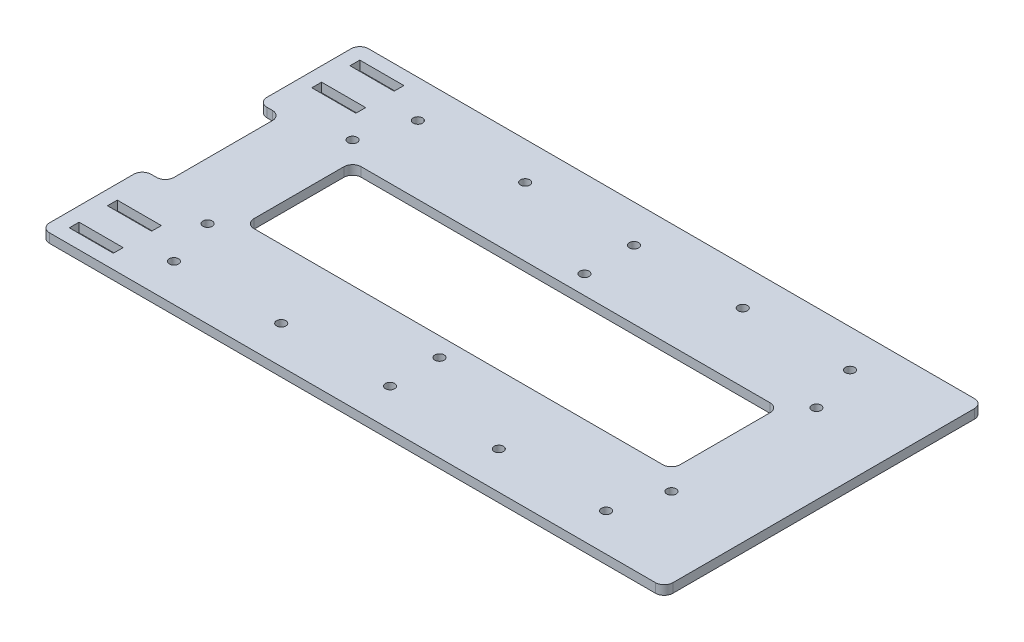
SolidWorks part; units mm, degrees
ref_plane "Front Plane" through (0, 0, 0) normal (0, 0, 1) x (1, 0, 0)
ref_plane "Top Plane" through (0, 0, 0) normal (0, 1, 0) x (1, 0, 0)
ref_plane "Right Plane" through (0, 0, 0) normal (1, 0, 0) x (0, 0, -1)
sketch "Sketch1" plane through (0, 0, 0) normal (0, 1, 0) x (1, 0, 0)
  line L1 (107.5, -55) -> (-107.5, -55)
  line L2 (107.5, -55) -> (107.5, 55)
  line L3 (107.5, 55) -> (-107.5, 55)
  line L4 (-107.5, -55) -> (-107.5, 55)
  line L5 (107.5, -55) -> (-107.5, 55) construction
  line L6 (107.5, 55) -> (-107.5, -55) construction
  point P0 (0, 0)
  dimension "D1" = 215
  dimension "D2" = 110
extrude "Boss-Extrude1" add sketch "Sketch1" along normal blind 3.175
sketch "Sketch2" plane through (0, 0, 0) normal (0, -1, 0) x (1, 0, 0)
  line L0 (71.5, -16.5) -> (71.5, 16.5) construction
  line L1 (-71.5, -16.5) -> (-71.5, 16.5) construction
  line L2 (71.5, -16.5) -> (-71.5, -16.5) construction
  line L3 (71.5, -16.5) -> (71.5, 16.5) construction
  line L4 (71.5, 16.5) -> (-71.5, 16.5)
  line L5 (-71.5, 16.5) -> (-71.5, -16.5)
  line L6 (-71.5, -16.5) -> (71.5, -16.5)
  line L7 (71.5, -16.5) -> (71.5, 16.5)
  line L8 (71.5, 16.5) -> (-71.5, 16.5) construction
  line L9 (-71.5, 16.5) -> (-71.5, -16.5) construction
  line L10 (-71.5, -16.5) -> (71.5, -16.5) construction
  line L11 (71.5, -16.5) -> (71.5, 16.5)
  line L12 (-71.5, -16.5) -> (-71.5, 16.5)
  line L13 (71.5, -16.5) -> (-71.5, -16.5)
  line L14 (73.5, -18.5) -> (73.5, 18.5)
  line L15 (73.5, 18.5) -> (-73.5, 18.5)
  line L16 (-73.5, 18.5) -> (-73.5, -18.5)
  line L17 (-73.5, -18.5) -> (73.5, -18.5)
  dimension "D1" = 0
  dimension "D2" = 2
extrude "Cut-Extrude1" cut sketch "Sketch2" against normal through all
sketch "Sketch3" plane through (0, 3.175, 0) normal (0, 1, 0) x (1, 0, 0)
  line L0 (-100.6, -19) -> (-107.5, -19) construction
  line L1 (-107.5, 55) -> (-107.5, -55) construction
  line L2 (-100.6, 19) -> (-107.5, 19) construction
  line L3 (-99.6, 20) -> (-107.5, 20)
  line L4 (-100.6, -19) -> (-100.6, 19)
  line L5 (-100.6, 19) -> (-102.5, 19)
  line L6 (-102.5, 19) -> (-102.5, -19)
  line L7 (-102.5, -19) -> (-100.6, -19)
  line L8 (-100.6, -19) -> (-100.6, 19) construction
  line L9 (-99.6, -20) -> (-99.6, 20)
  line L10 (-99.6, -20) -> (-107.5, -20)
  line L11 (-107.5, -20) -> (-107.5, 20)
  dimension "D1" = 0
  dimension "D2" = 1
extrude "Cut-Extrude2" cut sketch "Sketch3" against normal through all
sketch "Sketch5" plane through (0, 3.175, 0) normal (0, 1, 0) x (1, 0, 0)
  circle A0 centre (80, 25) radius 1.6 construction
  circle A1 centre (80, -25) radius 1.6 construction
  circle A2 centre (0, 25) radius 1.6 construction
  circle A3 centre (0, -25) radius 1.6 construction
  circle A4 centre (-80, 25) radius 1.6 construction
  circle A5 centre (-80, -25) radius 1.6 construction
  circle A6 centre (80, 25) radius 1.6
  circle A7 centre (80, -25) radius 1.6
  circle A8 centre (0, 25) radius 1.6
  circle A9 centre (0, -25) radius 1.6
  circle A10 centre (-80, 25) radius 1.6
  circle A11 centre (-80, -25) radius 1.6
extrude "Cut-Extrude4" cut sketch "Sketch5" against normal through all
sketch "Sketch6" plane through (0, 3.175, 0) normal (0, 1, 0) x (1, 0, 0)
  line L0 (-107.5, -42.0689) -> (107.5, -42.0689) construction
  line L1 (-107.5, -20) -> (-107.5, -55) construction
  line L2 (107.5, -55) -> (107.5, 55) construction
  line L3 (0, -42.0689) -> (0, 55) construction
  line L4 (107.5, 55) -> (-107.5, 55) construction
  line L5 (-99.6, 0) -> (107.5, 0) construction
  line L6 (-99.6, -20) -> (-99.6, 20) construction
  circle A0 centre (-74.5283, -42.0689) radius 1.6
  circle A1 centre (-37.5283, -42.0689) radius 1.6
  circle A2 centre (0, -42.0689) radius 1.6
  circle A3 centre (37.5283, -42.0689) radius 1.6
  circle A4 centre (74.5283, -42.0689) radius 1.6
  circle A5 centre (74.5283, 42.0689) radius 1.6
  circle A6 centre (37.5283, 42.0689) radius 1.6
  circle A7 centre (0, 42.0689) radius 1.6
  circle A8 centre (-37.5283, 42.0689) radius 1.6
  circle A9 centre (-74.5283, 42.0689) radius 1.6
  circle A10 centre (-0.5283, -42.0689) radius 1.6 [skipped]
  dimension "D1" = 3.2
  dimension "D2" = 3
extrude "Cut-Extrude5" cut sketch "Sketch6" against normal through all
sketch "Sketch7" plane through (0, 3.175, 0) normal (0, 1, 0) x (1, 0, 0)
  line L0 (-88.5, 46.825) -> (-87.5, 46.825) construction
  line L1 (-87.5, 46.825) -> (-87.5, 50) construction
  line L2 (-87.5, 50) -> (-88.5, 50) construction
  line L3 (-88.5, 50) -> (-101.5, 50) construction
  line L4 (-101.5, 46.825) -> (-88.5, 46.825) construction
  line L5 (-102.5, 46.825) -> (-101.5, 46.825) construction
  line L6 (-101.5, 50) -> (-102.5, 50) construction
  line L7 (-102.5, 50) -> (-102.5, 46.825) construction
  line L8 (-102.5, 33.65) -> (-101.5, 33.65) construction
  line L9 (-101.5, 36.825) -> (-102.5, 36.825) construction
  line L10 (-102.5, 36.825) -> (-102.5, 33.65) construction
  line L11 (-88.5, 33.65) -> (-87.5, 33.65) construction
  line L12 (-87.5, 33.65) -> (-87.5, 36.825) construction
  line L13 (-87.5, 36.825) -> (-88.5, 36.825) construction
  line L14 (-88.5, 36.825) -> (-101.5, 36.825) construction
  line L15 (-101.5, 33.65) -> (-88.5, 33.65) construction
  line L16 (-88.5, -36.825) -> (-87.5, -36.825) construction
  line L17 (-87.5, -36.825) -> (-87.5, -33.65) construction
  line L18 (-87.5, -33.65) -> (-88.5, -33.65) construction
  line L19 (-88.5, -33.65) -> (-101.5, -33.65) construction
  line L20 (-101.5, -36.825) -> (-88.5, -36.825) construction
  line L21 (-102.5, -36.825) -> (-101.5, -36.825) construction
  line L22 (-101.5, -33.65) -> (-102.5, -33.65) construction
  line L23 (-102.5, -33.65) -> (-102.5, -36.825) construction
  line L24 (-102.5, -50) -> (-101.5, -50) construction
  line L25 (-101.5, -46.825) -> (-102.5, -46.825) construction
  line L26 (-102.5, -46.825) -> (-102.5, -50) construction
  line L27 (-88.5, -46.825) -> (-101.5, -46.825) construction
  line L28 (-101.5, -50) -> (-88.5, -50) construction
  line L29 (-88.5, -50) -> (-87.5, -50) construction
  line L30 (-87.5, -50) -> (-87.5, -46.825) construction
  line L31 (-87.5, -46.825) -> (-88.5, -46.825) construction
  line L32 (-88.5, 46.825) -> (-87.5, 46.825) construction
  line L33 (-87.5, 46.825) -> (-87.5, 50) construction
  line L34 (-87.5, 50) -> (-88.5, 50) construction
  line L35 (-88.5, 50) -> (-101.5, 50) construction
  line L36 (-101.5, 46.825) -> (-88.5, 46.825) construction
  line L37 (-102.5, 46.825) -> (-101.5, 46.825) construction
  line L38 (-101.5, 50) -> (-102.5, 50) construction
  line L39 (-102.5, 50) -> (-102.5, 46.825) construction
  line L40 (-102.5, 33.65) -> (-101.5, 33.65) construction
  line L41 (-101.5, 36.825) -> (-102.5, 36.825) construction
  line L42 (-102.5, 36.825) -> (-102.5, 33.65) construction
  line L43 (-88.5, 33.65) -> (-87.5, 33.65) construction
  line L44 (-87.5, 33.65) -> (-87.5, 36.825) construction
  line L45 (-87.5, 36.825) -> (-88.5, 36.825) construction
  line L46 (-88.5, 36.825) -> (-101.5, 36.825) construction
  line L47 (-101.5, 33.65) -> (-88.5, 33.65) construction
  line L48 (-88.5, -36.825) -> (-87.5, -36.825) construction
  line L49 (-87.5, -36.825) -> (-87.5, -33.65) construction
  line L50 (-87.5, -33.65) -> (-88.5, -33.65) construction
  line L51 (-88.5, -33.65) -> (-101.5, -33.65) construction
  line L52 (-101.5, -36.825) -> (-88.5, -36.825) construction
  line L53 (-102.5, -36.825) -> (-101.5, -36.825) construction
  line L54 (-101.5, -33.65) -> (-102.5, -33.65) construction
  line L55 (-102.5, -33.65) -> (-102.5, -36.825) construction
  line L56 (-102.5, -50) -> (-101.5, -50) construction
  line L57 (-101.5, -46.825) -> (-102.5, -46.825) construction
  line L58 (-102.5, -46.825) -> (-102.5, -50) construction
  line L59 (-88.5, -46.825) -> (-101.5, -46.825) construction
  line L60 (-101.5, -50) -> (-88.5, -50) construction
  line L61 (-88.5, -50) -> (-87.5, -50) construction
  line L62 (-87.5, -50) -> (-87.5, -46.825) construction
  line L63 (-87.5, -46.825) -> (-88.5, -46.825) construction
  line L64 (-88.5, 46.725) -> (-87.4, 46.725)
  line L65 (-87.4, 46.725) -> (-87.4, 50.1)
  line L66 (-87.4, 50.1) -> (-88.5, 50.1)
  line L67 (-88.5, 50.1) -> (-101.5, 50.1)
  line L68 (-101.5, 50.1) -> (-102.6, 50.1)
  line L69 (-102.6, 50.1) -> (-102.6, 46.725)
  line L70 (-102.6, 46.725) -> (-101.5, 46.725)
  line L71 (-101.5, 46.725) -> (-88.5, 46.725)
  line L72 (-102.6, 33.55) -> (-101.5, 33.55)
  line L73 (-101.5, 33.55) -> (-88.5, 33.55)
  line L74 (-88.5, 33.55) -> (-87.4, 33.55)
  line L75 (-87.4, 33.55) -> (-87.4, 36.925)
  line L76 (-87.4, 36.925) -> (-88.5, 36.925)
  line L77 (-88.5, 36.925) -> (-101.5, 36.925)
  line L78 (-101.5, 36.925) -> (-102.6, 36.925)
  line L79 (-102.6, 36.925) -> (-102.6, 33.55)
  line L80 (-88.5, -36.925) -> (-87.4, -36.925)
  line L81 (-87.4, -36.925) -> (-87.4, -33.55)
  line L82 (-87.4, -33.55) -> (-88.5, -33.55)
  line L83 (-88.5, -33.55) -> (-101.5, -33.55)
  line L84 (-101.5, -33.55) -> (-102.6, -33.55)
  line L85 (-102.6, -33.55) -> (-102.6, -36.925)
  line L86 (-102.6, -36.925) -> (-101.5, -36.925)
  line L87 (-101.5, -36.925) -> (-88.5, -36.925)
  line L88 (-102.6, -50.1) -> (-101.5, -50.1)
  line L89 (-101.5, -50.1) -> (-88.5, -50.1)
  line L90 (-88.5, -50.1) -> (-87.4, -50.1)
  line L91 (-87.4, -50.1) -> (-87.4, -46.725)
  line L92 (-87.4, -46.725) -> (-88.5, -46.725)
  line L93 (-88.5, -46.725) -> (-101.5, -46.725)
  line L94 (-101.5, -46.725) -> (-102.6, -46.725)
  line L95 (-102.6, -46.725) -> (-102.6, -50.1)
  dimension "D1" = 0.1
extrude "Cut-Extrude6" cut sketch "Sketch7" against normal through all
fillet "Fillet1" radius 3 12 edges at (-107.5, 1.5875, 55) (107.5, 1.5875, 55) (107.5, 1.5875, -55) (-107.5, 1.5875, -55) (-107.5, 1.5875, -20) (-99.6, 1.5875, -20) (-99.6, 1.5875, 20) (-107.5, 1.5875, 20) (-73.5, 1.5875, 18.5) (73.5, 1.5875, 18.5) (73.5, 1.5875, -18.5) (-73.5, 1.5875, -18.5)
